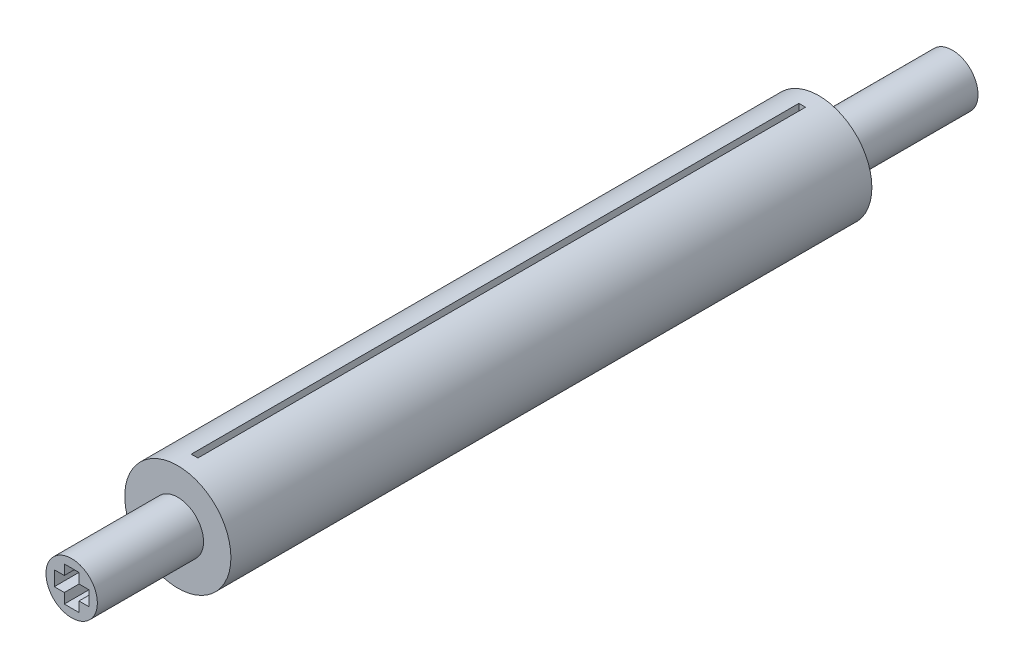
SolidWorks part; units mm, degrees
ref_plane "Front Plane" through (0, 0, 0) normal (0, 0, 1) x (1, 0, 0)
ref_plane "Top Plane" through (0, 0, 0) normal (0, 1, 0) x (1, 0, 0)
ref_plane "Right Plane" through (0, 0, 0) normal (1, 0, 0) x (0, 0, -1)
sketch "Sketch1" plane through (0, 0, 0) normal (0, 0, 1) x (1, 0, 0)
  circle A0 centre (0, 0) radius 7.95
  dimension "D1" = 15.9
extrude "Boss-Extrude1" add sketch "Sketch1" along normal mid plane 96
sketch "Sketch3" plane through (0, 0, 48) normal (0, 0, 1) x (1, 0, 0)
  circle A0 centre (0, 0) radius 3.85
  dimension "D1" = 7.7
extrude "Boss-Extrude2" add sketch "Sketch3" along normal blind 15.9
sketch "Sketch8" plane through (0, 0, -48) normal (0, 0, -1) x (-1, 0, 0)
  circle A0 centre (0, 0) radius 3.85
  dimension "D1" = 7.7
extrude "Boss-Extrude3" add sketch "Sketch8" along normal blind 20
sketch "Sketch6" plane through (0, 0, 63.9) normal (0, 0, 1) x (1, 0, 0)
  line L0 (0, 2.6) -> (0, -2.6) construction
  line L1 (0, -55) -> (0, 55) construction
  line L2 (-2.6, 0) -> (2.6, 0) construction
  line L3 (55, 0) -> (-55, 0) construction
  line L4 (-1.1, 2.6) -> (1.1, 2.6)
  line L5 (-1.1, 2.6) -> (-1.1, 1.1)
  line L6 (-1.1, 1.1) -> (-2.6, 1.1)
  line L7 (-2.6, 1.1) -> (-2.6, -1.1)
  line L8 (-2.6, -1.1) -> (-1.1, -1.1)
  line L9 (-1.1, -1.1) -> (-1.1, -2.6)
  line L10 (-1.1, -2.6) -> (1.1, -2.6)
  line L11 (1.1, -2.6) -> (1.1, -1.1)
  line L12 (1.1, -1.1) -> (2.6, -1.1)
  line L13 (2.6, -1.1) -> (2.6, 1.1)
  line L14 (2.6, 1.1) -> (1.1, 1.1)
  line L15 (1.1, 1.1) -> (1.1, 2.6)
  dimension "D1" = 5.2
  dimension "D2" = 2.2
extrude "Cut-Extrude2" cut sketch "Sketch6" against normal blind 15.1
ref_plane "Plane1" through (0, 7.95, 0) normal (0, 1, 0) x (1, 0, 0)
sketch "Sketch4" plane through (0, 7.95, 0) normal (0, 1, 0) x (1, 0, 0)
  line L5 (0, 48) -> (0, 45.5) construction
  line L6 (7.95, 48) -> (-7.95, 48) construction
  line L9 (0, -55) -> (0, 55) construction
  line L10 (0, -48) -> (0, -45.5) construction
  line L11 (-0.5, 45.5) -> (0.5, 45.5)
  line L12 (-0.5, 45.5) -> (-0.5, -45.5)
  line L13 (-0.5, -45.5) -> (0.5, -45.5)
  line L14 (0.5, 45.5) -> (0.5, -45.5)
  line L15 (-0.5, 45.5) -> (0.5, -45.5) construction
  line L16 (-0.5, -45.5) -> (0.5, 45.5) construction
  line L17 (-3.85, -48) -> (3.85, -48) construction
  point P10 (0, 0)
  dimension "D1" = 91
  dimension "D2" = 1
extrude "Cut-Extrude1" cut sketch "Sketch4" against normal blind 10
equation "\"D1@Cut-Extrude2\"=23.9-8.8mm"
equation "\"D1@Boss-Extrude2\"=15.1+0.3"
equation "\"D1@Sketch6\"=4.9+0.3"
equation "\"D2@Sketch6\"=1.9+0.3"
